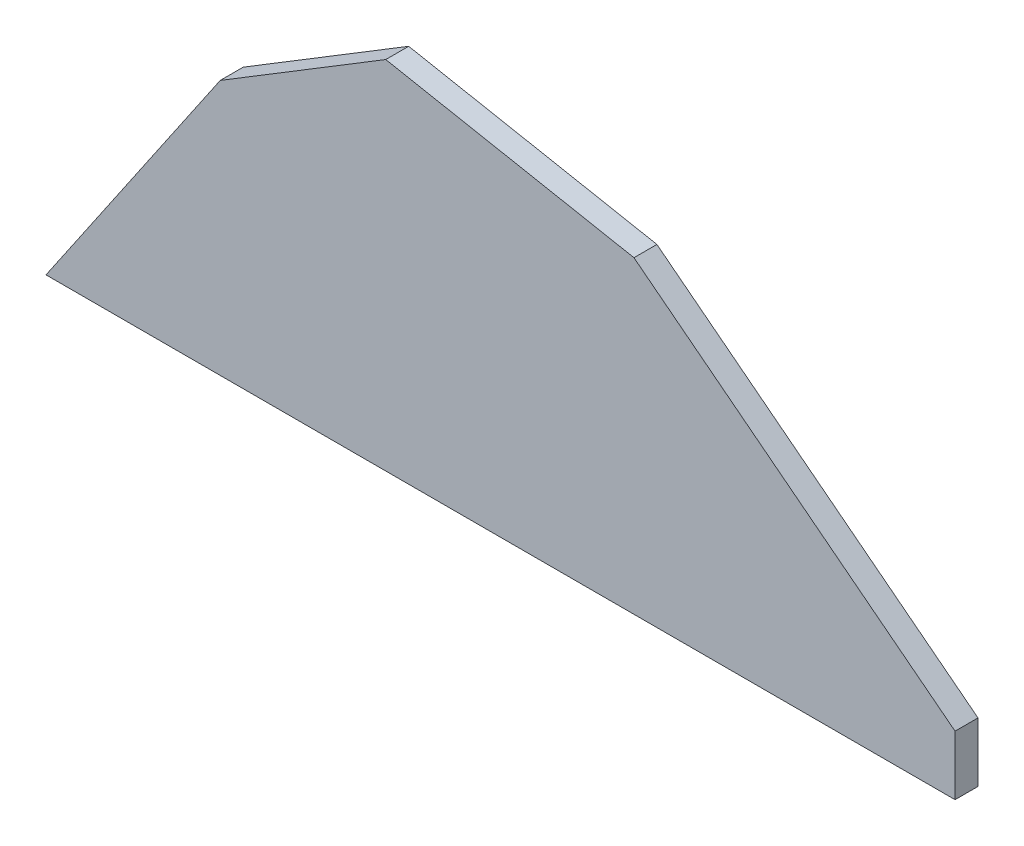
SolidWorks part; units mm, degrees
material "Oak"
ref_plane "Front Plane" through (0, 0, 0) normal (0, 0, 1) x (1, 0, 0)
ref_plane "Top Plane" through (0, 0, 0) normal (0, 1, 0) x (1, 0, 0)
ref_plane "Right Plane" through (0, 0, 0) normal (1, 0, 0) x (0, 0, -1)
sketch "Sketch1" plane through (0, 0, 0) normal (0, 0, 1) x (1, 0, 0)
  line L0 (-99.06, -36.437) -> (99.06, -36.437)
  line L1 (99.06, -36.437) -> (99.06, -23.4957)
  line L2 (99.06, -23.4957) -> (29.083, 30.873)
  line L3 (29.083, 30.873) -> (-25.019, 41.2235)
  line L4 (-25.019, 41.2235) -> (-61.087, 19.2525)
  line L5 (-61.087, 19.2525) -> (-99.06, -36.437)
  line L6 (0, -36.437) -> (0, 36.437) construction
  point P2 (0, 0)
  dimension "D1" = 198.12
  dimension "D2" = 12.9413
  dimension "D3" = 69.977
  dimension "D4" = 67.31
  dimension "D5" = 77.6605
  dimension "D6" = 74.041
  dimension "D7" = 37.973
  dimension "D8" = 55.6895
extrude "Boss-Extrude1" add sketch "Sketch1" along normal mid plane 5
